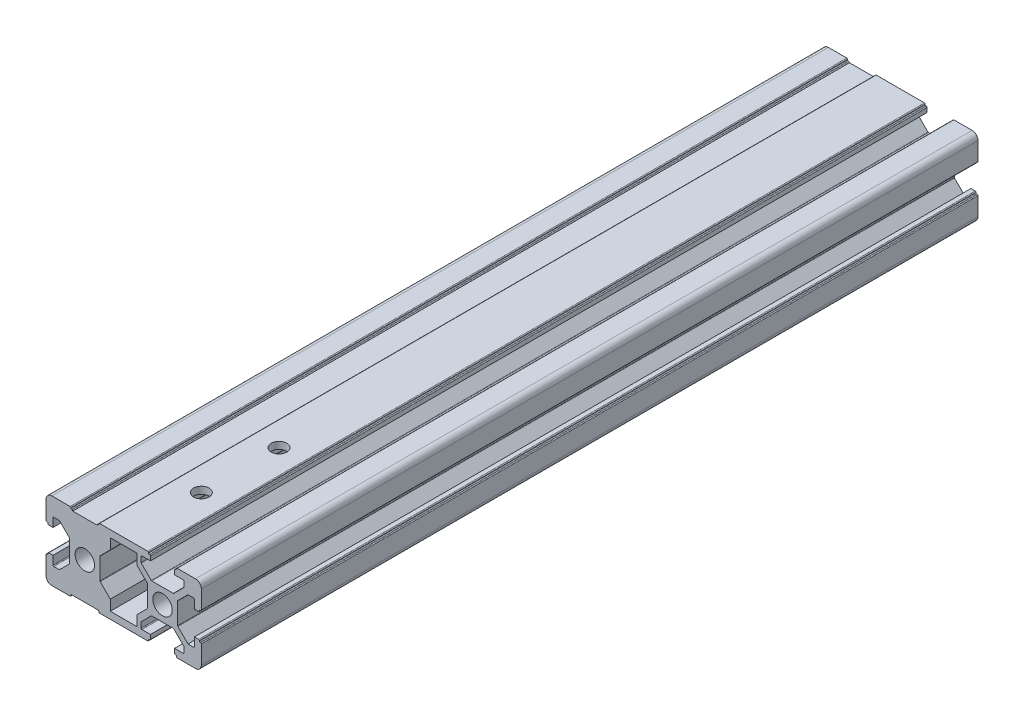
SolidWorks part; units mm, degrees
ref_plane "前视基准面" through (0, 0, 0) normal (0, 0, 1) x (1, 0, 0)
ref_plane "上视基准面" through (0, 0, 0) normal (0, 1, 0) x (1, 0, 0)
ref_plane "右视基准面" through (0, 0, 0) normal (1, 0, 0) x (0, 0, -1)
sketch "Sketch1" plane through (0, 0, 0) normal (0, 0, 1) x (1, 0, 0)
  line L0 (-8.5, 10) -> (-3.8, 10)
  line L3 (-8.5, -10) -> (-3.8, -10)
  line L5 (-10, 8.5) -> (-10, 3.8)
  line L10 (3.9, 2.7565) -> (3.9, -2.7565)
  line L11 (-3.9, 2.7565) -> (-3.9, -2.7565)
  line L12 (-3.9586, -2.8979) -> (-6.5607, -5.5)
  line L13 (3.6, 9.7) -> (3.6, 9.8)
  line L21 (-3.4, -9.5) -> (-3.3, -9.5)
  line L22 (3.8, -10) -> (8.5, -10)
  line L23 (3.3, -9.5) -> (3.4, -9.5)
  line L24 (-3.6, -9.7) -> (-3.6, -9.8)
  line L25 (3.6, -9.7) -> (3.6, -9.8)
  line L26 (-6.5607, -5.5) -> (-8, -5.5)
  line L27 (-9.7, -3.6) -> (-9.8, -3.6)
  line L28 (-9.5, -3.4) -> (-9.5, -3.3)
  line L29 (-8.2, -3.1) -> (-9.3, -3.1)
  line L30 (-8.2, -5.3) -> (-8.2, -3.1)
  line L31 (-10, -3.8) -> (-10, -8.5)
  line L33 (3.8, 10) -> (8.5, 10)
  line L40 (3.9586, -2.8979) -> (6.5607, -5.5)
  line L41 (3.3, 9.5) -> (3.4, 9.5)
  line L42 (30, 8.5) -> (30, 3.8)
  line L52 (3.9586, 2.8979) -> (6.5607, 5.5)
  line L53 (-3.6, 9.7) -> (-3.6, 9.8)
  line L54 (-3.4, 9.5) -> (-3.3, 9.5)
  line L59 (-9.5, 3.4) -> (-9.5, 3.3)
  line L60 (-9.7, 3.6) -> (-9.8, 3.6)
  line L61 (-8.2, 3.1) -> (-9.3, 3.1)
  line L62 (-8.2, 5.3) -> (-8.2, 3.1)
  line L63 (-6.5607, 5.5) -> (-8, 5.5)
  line L64 (-3.9586, 2.8979) -> (-6.5607, 5.5)
  line L65 (29.7, 3.6) -> (29.8, 3.6)
  line L66 (29.5, 3.4) -> (29.5, 3.3)
  line L67 (28.2, 3.1) -> (29.3, 3.1)
  line L68 (28.2, 5.3) -> (28.2, 3.1)
  line L69 (26.5607, 5.5) -> (28, 5.5)
  line L70 (23.9586, 2.8979) -> (26.5607, 5.5)
  line L71 (23.9, 2.7565) -> (23.9, -2.7565)
  line L72 (23.9586, -2.8979) -> (26.5607, -5.5)
  line L73 (26.5607, -5.5) -> (28, -5.5)
  line L74 (28.2, -5.3) -> (28.2, -3.1)
  line L75 (28.2, -3.1) -> (29.3, -3.1)
  line L76 (29.5, -3.4) -> (29.5, -3.3)
  line L77 (29.7, -3.6) -> (29.8, -3.6)
  line L78 (30, -3.8) -> (30, -8.5)
  line L79 (28.5, -10) -> (23.8, -10)
  line L80 (23.6, -9.7) -> (23.6, -9.8)
  line L81 (23.4, -9.5) -> (23.3, -9.5)
  line L82 (23.1, -8.2) -> (23.1, -9.3)
  line L83 (25.3, -8.2) -> (23.1, -8.2)
  line L84 (25.5, -6.5607) -> (25.5, -8)
  line L85 (22.8979, -3.9586) -> (25.5, -6.5607)
  line L86 (22.7565, -3.9) -> (17.2435, -3.9)
  line L87 (17.1021, -3.9586) -> (14.5, -6.5607)
  line L88 (14.5, -6.5607) -> (14.5, -8)
  line L89 (16.9, -8.2) -> (14.7, -8.2)
  line L90 (16.9, -8.2) -> (16.9, -9.3)
  line L91 (16.7, -9.5) -> (16.6, -9.5)
  line L92 (16.4, -9.7) -> (16.4, -9.8)
  line L93 (16.2, -10) -> (11.5, -10)
  line L94 (13.4393, 5.5) -> (13.4393, 8.2)
  line L96 (6.5607, 5.5) -> (6.5607, 8.2)
  line L97 (6.5607, 8.2) -> (13.4393, 8.2)
  line L99 (16.0414, -2.8979) -> (13.4393, -5.5)
  line L100 (16.1, 2.7565) -> (16.1, -2.7565)
  line L101 (16.0414, 2.8979) -> (13.4393, 5.5)
  line L107 (16.2, 10) -> (11.5, 10)
  line L108 (16.4, 9.7) -> (16.4, 9.8)
  line L109 (16.7, 9.5) -> (16.6, 9.5)
  line L110 (16.9, 8.2) -> (16.9, 9.3)
  line L111 (16.9, 8.2) -> (14.7, 8.2)
  line L112 (14.5, 6.5607) -> (14.5, 8)
  line L113 (17.1021, 3.9586) -> (14.5, 6.5607)
  line L114 (22.7565, 3.9) -> (17.2435, 3.9)
  line L115 (22.8979, 3.9586) -> (25.5, 6.5607)
  line L116 (25.5, 6.5607) -> (25.5, 8)
  line L117 (25.3, 8.2) -> (23.1, 8.2)
  line L118 (23.1, 8.2) -> (23.1, 9.3)
  line L119 (23.4, 9.5) -> (23.3, 9.5)
  line L120 (23.6, 9.7) -> (23.6, 9.8)
  line L121 (28.5, 10) -> (23.8, 10)
  line L122 (13.4393, -5.5) -> (13.4393, -8.2)
  line L124 (6.5607, -5.5) -> (6.5607, -8.2)
  line L125 (6.5607, -8.2) -> (13.4393, -8.2)
  line L127 (8.5, 10) -> (11.5, 10)
  line L128 (8.5, -10) -> (11.5, -10)
  line L129 (-3.3, -9.5) -> (3.3, -9.5)
  line L130 (-3.1, 9.3) -> (3.1, 9.3)
  arc A3 (-8.5, -10) -> (-10, -8.5) centre (-8.5, -8.5) cw
  arc A4 (-10, 8.5) -> (-8.5, 10) centre (-8.5, 8.5) cw
  arc A5 (3.4, -9.5) -> (3.6, -9.7) centre (3.4, -9.7) cw
  arc A6 (3.8, -10) -> (3.6, -9.8) centre (3.8, -9.8) cw
  arc A9 (-3.9, -2.7565) -> (-3.9586, -2.8979) centre (-4.1, -2.7565) cw
  arc A10 (-3.9, 2.7565) -> (-3.9586, 2.8979) centre (-4.1, 2.7565) ccw
  arc A13 (3.9586, 2.8979) -> (3.9, 2.7565) centre (4.1, 2.7565) ccw
  arc A14 (3.9, -2.7565) -> (3.9586, -2.8979) centre (4.1, -2.7565) ccw
  arc A17 (-3.6, -9.8) -> (-3.8, -10) centre (-3.8, -9.8) cw
  arc A19 (-3.6, -9.7) -> (-3.4, -9.5) centre (-3.4, -9.7) cw
  arc A20 (-8.2, 5.3) -> (-8, 5.5) centre (-8, 5.3) cw
  arc A23 (-8.2, -5.3) -> (-8, -5.5) centre (-8, -5.3) ccw
  arc A31 (3.1, 9.3) -> (3.3, 9.5) centre (3.3, 9.3) cw
  arc A32 (3.6, 9.8) -> (3.8, 10) centre (3.8, 9.8) cw
  arc A33 (3.6, 9.7) -> (3.4, 9.5) centre (3.4, 9.7) cw
  arc A34 (-3.8, 10) -> (-3.6, 9.8) centre (-3.8, 9.8) cw
  arc A35 (-3.3, 9.5) -> (-3.1, 9.3) centre (-3.3, 9.3) cw
  arc A36 (-3.4, 9.5) -> (-3.6, 9.7) centre (-3.4, 9.7) cw
  arc A39 (-10, 3.8) -> (-9.8, 3.6) centre (-9.8, 3.8) ccw
  arc A40 (-9.5, 3.3) -> (-9.3, 3.1) centre (-9.3, 3.3) ccw
  arc A41 (-9.7, 3.6) -> (-9.5, 3.4) centre (-9.7, 3.4) cw
  arc A42 (-10, -3.8) -> (-9.8, -3.6) centre (-9.8, -3.8) cw
  arc A43 (-9.5, -3.3) -> (-9.3, -3.1) centre (-9.3, -3.3) cw
  arc A44 (-9.5, -3.4) -> (-9.7, -3.6) centre (-9.7, -3.4) cw
  arc A45 (30, 8.5) -> (28.5, 10) centre (28.5, 8.5) ccw
  arc A46 (30, 3.8) -> (29.8, 3.6) centre (29.8, 3.8) cw
  arc A47 (29.7, 3.6) -> (29.5, 3.4) centre (29.7, 3.4) ccw
  arc A48 (29.5, 3.3) -> (29.3, 3.1) centre (29.3, 3.3) cw
  arc A49 (28.2, 5.3) -> (28, 5.5) centre (28, 5.3) ccw
  arc A50 (23.9, 2.7565) -> (23.9586, 2.8979) centre (24.1, 2.7565) cw
  arc A51 (23.9, -2.7565) -> (23.9586, -2.8979) centre (24.1, -2.7565) ccw
  arc A52 (28.2, -5.3) -> (28, -5.5) centre (28, -5.3) cw
  arc A53 (29.5, -3.3) -> (29.3, -3.1) centre (29.3, -3.3) ccw
  arc A54 (29.5, -3.4) -> (29.7, -3.6) centre (29.7, -3.4) ccw
  arc A55 (30, -3.8) -> (29.8, -3.6) centre (29.8, -3.8) ccw
  arc A56 (28.5, -10) -> (30, -8.5) centre (28.5, -8.5) ccw
  arc A57 (23.6, -9.8) -> (23.8, -10) centre (23.8, -9.8) ccw
  arc A58 (23.6, -9.7) -> (23.4, -9.5) centre (23.4, -9.7) ccw
  arc A59 (23.3, -9.5) -> (23.1, -9.3) centre (23.3, -9.3) cw
  arc A60 (25.3, -8.2) -> (25.5, -8) centre (25.3, -8) ccw
  arc A61 (22.8979, -3.9586) -> (22.7565, -3.9) centre (22.7565, -4.1) ccw
  arc A62 (17.2435, -3.9) -> (17.1021, -3.9586) centre (17.2435, -4.1) ccw
  arc A63 (14.7, -8.2) -> (14.5, -8) centre (14.7, -8) cw
  arc A64 (16.7, -9.5) -> (16.9, -9.3) centre (16.7, -9.3) ccw
  arc A65 (16.6, -9.5) -> (16.4, -9.7) centre (16.6, -9.7) ccw
  arc A66 (16.2, -10) -> (16.4, -9.8) centre (16.2, -9.8) ccw
  arc A72 (16.1, -2.7565) -> (16.0414, -2.8979) centre (15.9, -2.7565) cw
  arc A73 (16.0414, 2.8979) -> (16.1, 2.7565) centre (15.9, 2.7565) cw
  arc A79 (16.4, 9.8) -> (16.2, 10) centre (16.2, 9.8) ccw
  arc A80 (16.4, 9.7) -> (16.6, 9.5) centre (16.6, 9.7) ccw
  arc A81 (16.9, 9.3) -> (16.7, 9.5) centre (16.7, 9.3) ccw
  arc A82 (14.5, 8) -> (14.7, 8.2) centre (14.7, 8) cw
  arc A83 (17.2435, 3.9) -> (17.1021, 3.9586) centre (17.2435, 4.1) cw
  arc A84 (22.7565, 3.9) -> (22.8979, 3.9586) centre (22.7565, 4.1) ccw
  arc A85 (25.5, 8) -> (25.3, 8.2) centre (25.3, 8) ccw
  arc A86 (23.3, 9.5) -> (23.1, 9.3) centre (23.3, 9.3) ccw
  arc A87 (23.4, 9.5) -> (23.6, 9.7) centre (23.4, 9.7) ccw
  arc A88 (23.8, 10) -> (23.6, 9.8) centre (23.8, 9.8) ccw
  point P11 (3.9, 3.9)
  point P19 (3.3697, 4.4303)
  point P20 (-10.6428, -10.6428)
  point P25 (-11.1731, -10.1124)
  point P26 (4.4303, 3.3697)
  point P28 (-10.1124, -11.1731)
  dimension "D3" = 0.2
  dimension "D4" = 0.2
  dimension "D8" = 0.2
  dimension "D9" = 0.2
  dimension "D10" = 0.2
  dimension "D7" = 0.5
extrude "Boss-Extrude1" add sketch "Sketch1" along normal blind 200
ref_plane "hole" through (0, 0, 200) normal (0, 0, 1) x (1, 0, 0)
sketch "Sketch2" plane through (0, 0, 200) normal (0, 0, 1) x (1, 0, 0)
  circle A0 centre (0, 0) radius 2.5
  circle A1 centre (20, 0) radius 2.5
  dimension "D1" = 5
extrude "Cut-Extrude1" cut sketch "Sketch2" against normal through all
sketch "Sketch3" plane through (0, -10, 0) normal (0, -1, 0) x (-1, 0, 0)
  line L0 (-3.8, -200) -> (-16.2, -200) construction
  circle A0 centre (-10, -180) radius 2
  circle A1 centre (-10, -160) radius 2
  point P6 (-10, -200)
  dimension "D1" = 0
  dimension "D2" = 0
  dimension "D3" = 20
  dimension "D4" = 20
  dimension "D5" = 4
  dimension "D6" = 4
extrude "Cut-Extrude2" cut sketch "Sketch3" against normal blind 40
